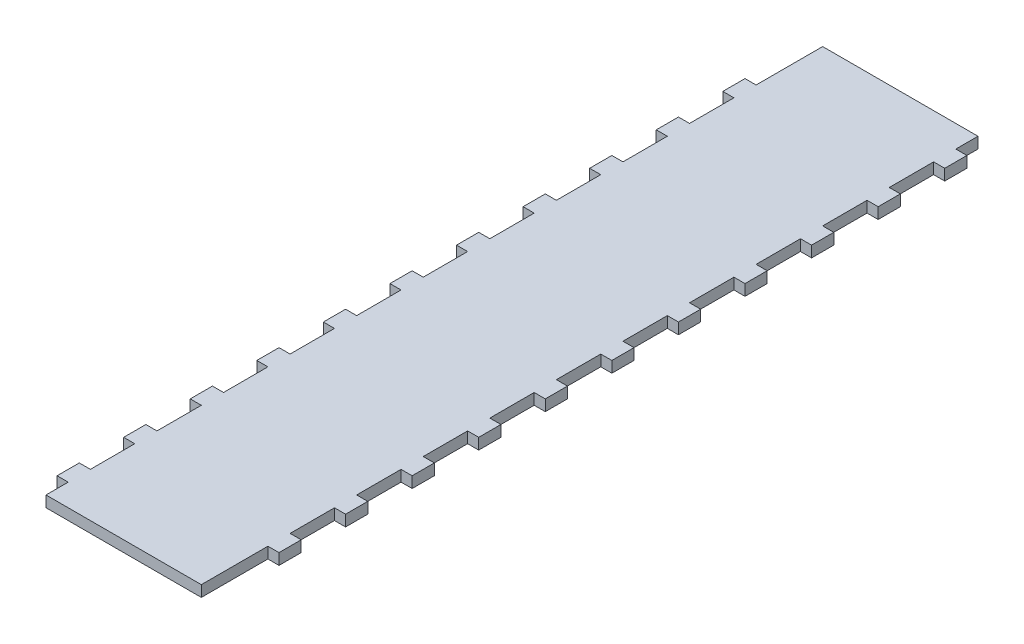
SolidWorks part; units mm, degrees
ref_plane "Front Plane" through (0, 0, 0) normal (0, 0, 1) x (1, 0, 0)
ref_plane "Top Plane" through (0, 0, 0) normal (0, 1, 0) x (1, 0, 0)
ref_plane "Right Plane" through (0, 0, 0) normal (1, 0, 0) x (0, 0, -1)
sketch "Sketch1" plane through (0, 0, 0) normal (0, 1, 0) x (1, 0, 0)
  line L0 (-238.1691, -88.7556) -> (-238.1691, -78.7556)
  line L1 (-238.1691, -118.7556) -> (-233.1691, -118.7556)
  line L2 (-233.1691, 221.2444) -> (-163.1691, 221.2444)
  line L4 (-238.1691, -78.7556) -> (-233.1691, -78.7556)
  line L6 (-233.1691, -78.7556) -> (-233.1691, -58.7556)
  line L7 (-233.1691, -58.7556) -> (-238.1691, -58.7556)
  line L8 (-238.1691, -58.7556) -> (-238.1691, -48.7556)
  line L9 (-238.1691, -48.7556) -> (-233.1691, -48.7556)
  line L10 (-238.1691, -118.7556) -> (-238.1691, -108.7556)
  line L11 (-238.1691, -108.7556) -> (-233.1691, -108.7556)
  line L12 (-233.1691, -108.7556) -> (-233.1691, -88.7556)
  line L13 (-233.1691, -88.7556) -> (-238.1691, -88.7556)
  line L14 (-233.1691, -48.7556) -> (-233.1691, -28.7556)
  line L15 (-233.1691, -28.7556) -> (-238.1691, -28.7556)
  line L16 (-238.1691, -28.7556) -> (-238.1691, -18.7556)
  line L17 (-238.1691, -18.7556) -> (-233.1691, -18.7556)
  line L18 (-233.1691, -18.7556) -> (-233.1691, 1.2444)
  line L19 (-233.1691, 1.2444) -> (-238.1691, 1.2444)
  line L20 (-238.1691, 1.2444) -> (-238.1691, 11.2444)
  line L21 (-238.1691, 11.2444) -> (-233.1691, 11.2444)
  line L22 (-233.1691, 11.2444) -> (-233.1691, 31.2444)
  line L23 (-233.1691, 31.2444) -> (-238.1691, 31.2444)
  line L24 (-238.1691, 31.2444) -> (-238.1691, 41.2444)
  line L25 (-238.1691, 41.2444) -> (-233.1691, 41.2444)
  line L26 (-233.1691, 41.2444) -> (-233.1691, 61.2444)
  line L27 (-233.1691, 61.2444) -> (-238.1691, 61.2444)
  line L28 (-238.1691, 61.2444) -> (-238.1691, 71.2444)
  line L29 (-238.1691, 71.2444) -> (-233.1691, 71.2444)
  line L30 (-233.1691, 71.2444) -> (-233.1691, 91.2444)
  line L31 (-233.1691, 91.2444) -> (-238.1691, 91.2444)
  line L32 (-238.1691, 91.2444) -> (-238.1691, 101.2444)
  line L33 (-238.1691, 101.2444) -> (-233.1691, 101.2444)
  line L34 (-233.1691, 101.2444) -> (-233.1691, 121.2444)
  line L35 (-233.1691, 121.2444) -> (-238.1691, 121.2444)
  line L36 (-238.1691, 121.2444) -> (-238.1691, 131.2444)
  line L37 (-238.1691, 131.2444) -> (-233.1691, 131.2444)
  line L38 (-233.1691, 131.2444) -> (-233.1691, 151.2444)
  line L39 (-233.1691, 151.2444) -> (-238.1691, 151.2444)
  line L40 (-238.1691, 151.2444) -> (-238.1691, 161.2444)
  line L41 (-238.1691, 161.2444) -> (-233.1691, 161.2444)
  line L42 (-233.1691, 161.2444) -> (-233.1691, 181.2444)
  line L43 (-233.1691, 181.2444) -> (-238.1691, 181.2444)
  line L44 (-238.1691, 181.2444) -> (-238.1691, 191.2444)
  line L45 (-238.1691, 191.2444) -> (-233.1691, 191.2444)
  line L46 (-233.1691, 191.2444) -> (-233.1691, 211.2444)
  line L47 (-233.1691, -118.7556) -> (-233.1691, -128.7556)
  line L48 (-158.1691, 211.2444) -> (-158.1691, 201.2444)
  line L49 (-158.1691, 201.2444) -> (-163.1691, 201.2444)
  line L50 (-163.1691, 201.2444) -> (-163.1691, 181.2444)
  line L51 (-163.1691, 181.2444) -> (-158.1691, 181.2444)
  line L52 (-158.1691, 181.2444) -> (-158.1691, 171.2444)
  line L53 (-158.1691, 171.2444) -> (-163.1691, 171.2444)
  line L54 (-163.1691, 171.2444) -> (-163.1691, 151.2444)
  line L55 (-163.1691, 151.2444) -> (-158.1691, 151.2444)
  line L56 (-158.1691, 151.2444) -> (-158.1691, 141.2444)
  line L57 (-158.1691, 141.2444) -> (-163.1691, 141.2444)
  line L58 (-163.1691, 141.2444) -> (-163.1691, 121.2444)
  line L59 (-163.1691, 121.2444) -> (-158.1691, 121.2444)
  line L60 (-158.1691, 121.2444) -> (-158.1691, 111.2444)
  line L62 (-158.1691, 111.2444) -> (-163.1691, 111.2444)
  line L63 (-163.1691, 111.2444) -> (-163.1691, 91.2444)
  line L64 (-163.1691, 91.2444) -> (-158.1691, 91.2444)
  line L65 (-158.1691, 91.2444) -> (-158.1691, 81.2444)
  line L66 (-158.1691, 81.2444) -> (-163.1691, 81.2444)
  line L67 (-163.1691, 81.2444) -> (-163.1691, 61.2444)
  line L68 (-163.1691, 61.2444) -> (-158.1691, 61.2444)
  line L69 (-158.1691, 61.2444) -> (-158.1691, 51.2444)
  line L70 (-158.1691, 51.2444) -> (-163.1691, 51.2444)
  line L71 (-163.1691, 51.2444) -> (-163.1691, 31.2444)
  line L72 (-163.1691, 31.2444) -> (-158.1691, 31.2444)
  line L73 (-158.1691, 31.2444) -> (-158.1691, 21.2444)
  line L74 (-158.1691, 21.2444) -> (-163.1691, 21.2444)
  line L75 (-163.1691, 21.2444) -> (-163.1691, 1.2444)
  line L76 (-163.1691, 1.2444) -> (-158.1691, 1.2444)
  line L77 (-158.1691, 1.2444) -> (-158.1691, -8.7556)
  line L78 (-158.1691, -8.7556) -> (-163.1691, -8.7556)
  line L79 (-163.1691, -8.7556) -> (-163.1691, -28.7556)
  line L80 (-163.1691, -28.7556) -> (-158.1691, -28.7556)
  line L81 (-158.1691, -28.7556) -> (-158.1691, -38.7556)
  line L82 (-158.1691, -38.7556) -> (-163.1691, -38.7556)
  line L83 (-163.1691, -38.7556) -> (-163.1691, -58.7556)
  line L84 (-163.1691, -58.7556) -> (-158.1691, -58.7556)
  line L85 (-158.1691, -58.7556) -> (-158.1691, -68.7556)
  line L86 (-158.1691, -68.7556) -> (-163.1691, -68.7556)
  line L87 (-163.1691, -68.7556) -> (-163.1691, -88.7556)
  line L88 (-163.1691, -88.7556) -> (-158.1691, -88.7556)
  line L89 (-158.1691, -88.7556) -> (-158.1691, -98.7556)
  line L90 (-158.1691, -98.7556) -> (-163.1691, -98.7556)
  line L91 (-163.1691, -98.7556) -> (-163.1691, -118.7556)
  line L93 (-158.1691, 211.2444) -> (-163.1691, 211.2444)
  line L94 (-163.1691, 211.2444) -> (-163.1691, 221.2444)
  line L95 (-233.1691, 211.2444) -> (-233.1691, 221.2444)
  line L96 (-233.1691, -128.7556) -> (-163.1691, -128.7556)
  line L98 (-163.1691, -118.7556) -> (-163.1691, -128.7556)
  line L118 (-233.1691, 211.2444) -> (-238.1691, 211.2444) [skipped]
  line L119 (-157.7361, -118.7556) -> (-152.7361, -118.7556) [skipped]
  dimension "D1" = 70
  dimension "D3" = 5
  dimension "D4" = 11
  dimension "D5" = 10
  dimension "D2" = 10
  dimension "D6" = 20
  dimension "D7" = 20
  dimension "D8" = 5
  dimension "D9" = 11
extrude "Boss-Extrude1" add sketch "Sketch1" along normal blind 5
